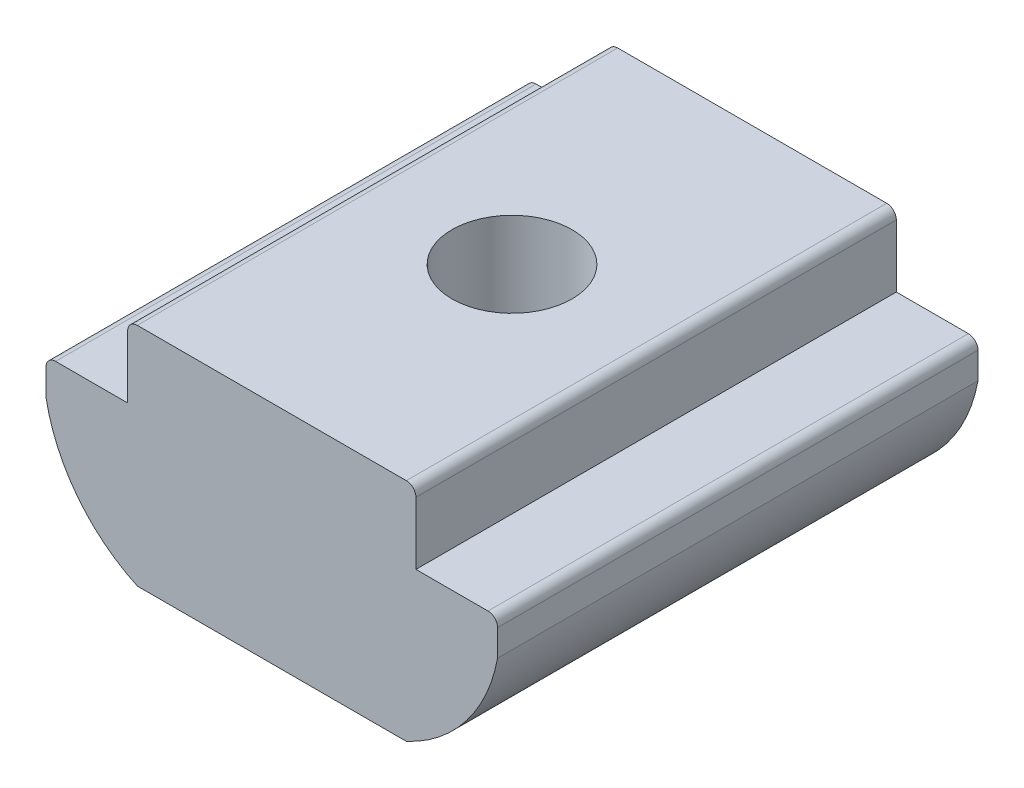
SolidWorks part; units mm, degrees
ref_plane "前视基准面" through (0, 0, 0) normal (0, 0, 1) x (1, 0, 0)
ref_plane "上视基准面" through (0, 0, 0) normal (0, 1, 0) x (1, 0, 0)
ref_plane "右视基准面" through (0, 0, 0) normal (1, 0, 0) x (0, 0, -1)
sketch "草图1" plane through (0, 0, 0) normal (0, 0, 1) x (1, 0, 0)
  line B0 (-2.8, 4.7) -> (2.8, 4.7)
  line B1 (4.7, 3) -> (4.7, 2.45)
  line B2 (-4.7, 3) -> (-4.7, 2.45)
  line B3 (-2.8, 0) -> (2.8, 0)
  line B4 (-4.5, 3.2) -> (-3, 3.2)
  line B5 (3, 3.2) -> (4.5, 3.2)
  line B6 (-3, 4.5) -> (-3, 3.2)
  line B7 (3, 4.5) -> (3, 3.2)
  arc B8 (-2.8, 4.7) -> (-3, 4.5) centre (-2.8, 4.5) ccw
  arc B9 (3, 4.5) -> (2.8, 4.7) centre (2.8, 4.5) ccw
  arc B10 (-4.5, 3.2) -> (-4.7, 3) centre (-4.5, 3) ccw
  arc B11 (4.7, 3) -> (4.5, 3.2) centre (4.5, 3) ccw
  arc B12 (-4.7, 2.45) -> (-2.8, 0) centre (-1.3774, 3.0649) ccw
  arc B13 (2.8, 0) -> (4.7, 2.45) centre (1.3774, 3.0649) ccw
sketch_block_instance "A$C334B3D09-1"
sketch_block "A$C334B3D09"
extrude "凸台-拉伸1" add sketch "草图1" along normal mid plane 10
sketch "草图3" plane through (0, 4.7, 0) normal (0, 1, 0) x (1, 0, 0)
  point P0 (0, 0)
hole_wizard "M3螺纹孔" positions "3D草图1" profile "草图4" tap size "M3" standard "ISO"
sketch3d "3D草图1"
  point P0 (0, 4.7, 0)
sketch "草图4" plane through (0, 4.7, 0) normal (1, 0, 0) x (0, 0, 1)
  line L0 (0, 0) -> (0, 8.2511)
  line L1 (0, 8.2511) -> (1.25, 7.5)
  line L2 (1.25, 7.5) -> (1.25, 0)
  line L5 (1.25, 0) -> (0, 0)
  line L10 (0, 8.2511) -> (-1.25, 7.5) construction
  line L11 (0, -6.35) -> (0, 107.95) construction
  dimension "螺纹孔钻头直径" = 2.5
  dimension "螺纹孔钻头深度" = 7.5
  dimension "导头角度" = 118
cosmetic thread "孔螺蚊线1" parameters "D1"=4.7, "D2"=3
